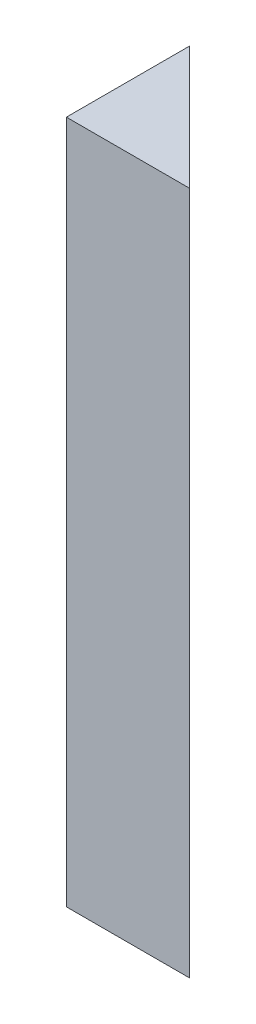
SolidWorks part; units mm, degrees
ref_plane "Front Plane" through (0, 0, 0) normal (0, 0, 1) x (1, 0, 0)
ref_plane "Top Plane" through (0, 0, 0) normal (0, 1, 0) x (1, 0, 0)
ref_plane "Right Plane" through (0, 0, 0) normal (1, 0, 0) x (0, 0, -1)
sketch "Sketch2" plane through (0, 0, 0) normal (0, 1, 0) x (1, 0, 0)
  line L0 (-10, 10) -> (10, -10)
  line L1 (10, 10) -> (-10, 10)
  line L2 (10, 10) -> (10, -10)
  line L3 (10, -10) -> (-10, -10)
  line L4 (-10, 10) -> (-10, -10)
  line L5 (10, 10) -> (-10, -10) construction
  line L6 (10, -10) -> (-10, 10) construction
  point P0 (0, 0)
  dimension "D1" = 20
  dimension "D2" = 20
extrude "Boss-Extrude1" add sketch "Sketch2" along normal blind 111 contours L0 L4 L3
